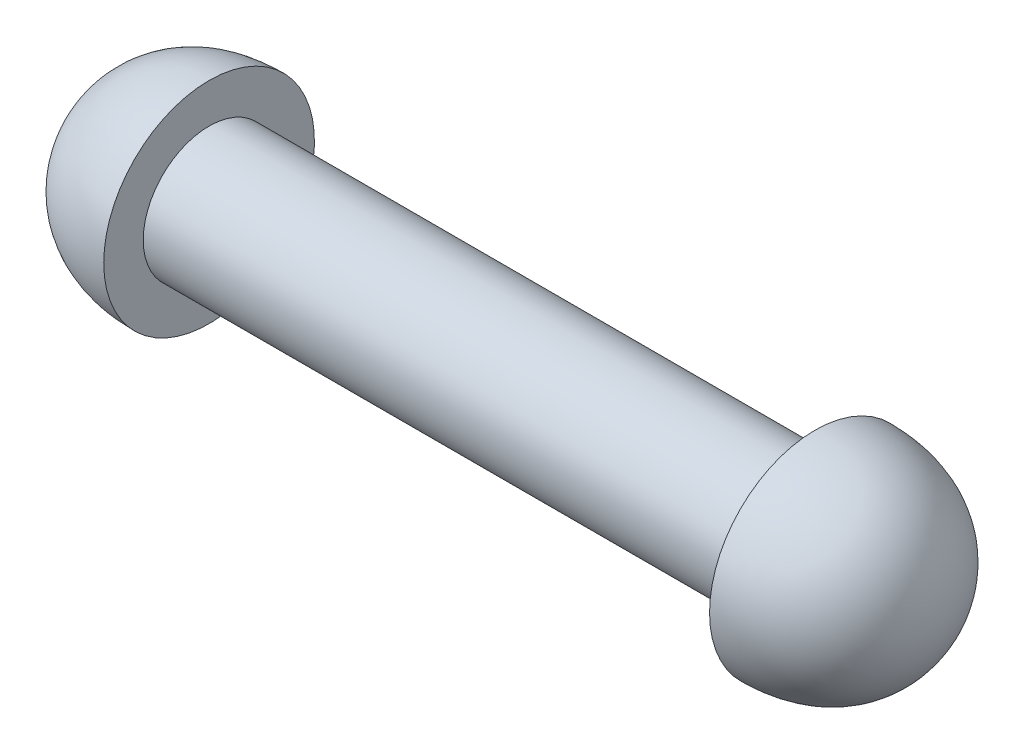
SolidWorks part; units mm, degrees
material "Plain Carbon Steel"
ref_plane "Front Plane" through (0, 0, 0) normal (0, 0, 1) x (1, 0, 0)
ref_plane "Top Plane" through (0, 0, 0) normal (0, 1, 0) x (1, 0, 0)
ref_plane "Right Plane" through (0, 0, 0) normal (1, 0, 0) x (0, 0, -1)
sketch "Sketch1" plane through (0, 0, 0) normal (1, 0, 0) x (0, 0, -1)
  circle A0 centre (0, 0) radius 25
  dimension "D1" = 50
extrude "Boss-Extrude1" add sketch "Sketch1" along normal blind 115
sketch "Sketch3" plane through (0, 0, 0) normal (0, 0, 1) x (1, 0, 0)
  line L2 (-100.0787, 0) -> (83.5342, 0) construction
  line L3 (0, 0) -> (-45.4584, 0)
  line L4 (0, 40) -> (0, 0)
  spline S0 degree 3 poles (-45.4584, 0) (-45.4584, 20.1838) (-30.9912, 40) (0, 40) knots 0 0 0 0 1 1 1 1
  dimension "D1" = 40
revolve "Revolve1" add sketch "Sketch3" angle 360 about L2
mirror "Mirror1" about plane through (115, 0, 0) normal (1, 0, 0) of "Boss-Extrude1", "Revolve1"
